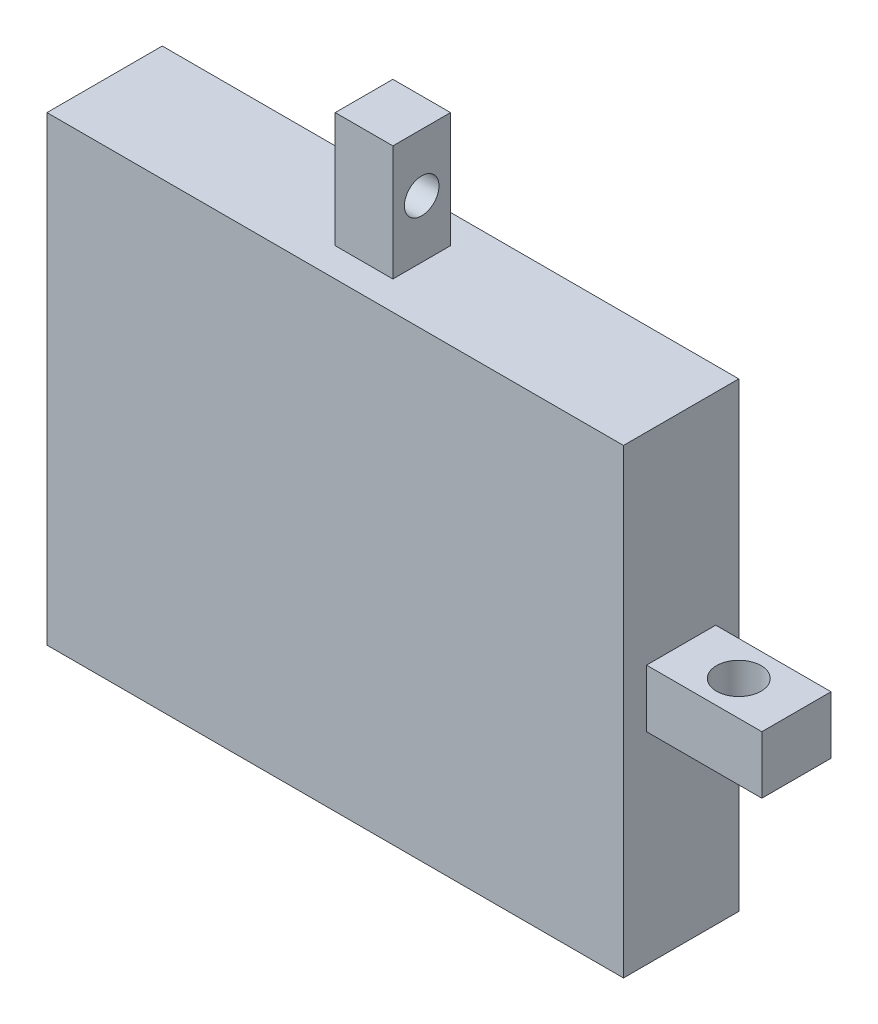
SolidWorks part; units mm, degrees
ref_plane "Front Plane" through (0, 0, 0) normal (0, 0, 1) x (1, 0, 0)
ref_plane "Top Plane" through (0, 0, 0) normal (0, 1, 0) x (1, 0, 0)
ref_plane "Right Plane" through (0, 0, 0) normal (1, 0, 0) x (0, 0, -1)
sketch "Sketch1" plane through (669.8418, 0, 0) normal (0, 0, 1) x (1, 0, 0)
  line L1 (-696.3103, 457.6379) -> (-646.3103, 457.6379)
  line L2 (-696.3103, 457.6379) -> (-696.3103, 417.6379)
  line L3 (-696.3103, 417.6379) -> (-646.3103, 417.6379)
  line L4 (-646.3103, 457.6379) -> (-646.3103, 417.6379)
  dimension "50" = 50
  dimension "D2" = 40
extrude "Boss-Extrude1" add sketch "Sketch1" along normal blind 10
sketch "Sketch5" plane through (23.5315, 0, 0) normal (1, 0, 0) x (0, 0, -1)
  line L0 (0, 417.6379) -> (0, 457.6379) construction
  line L1 (-8, 445.1379) -> (-2, 445.1379)
  line L2 (-8, 445.1379) -> (-8, 440.1379)
  line L3 (-8, 440.1379) -> (-2, 440.1379)
  line L4 (-2, 445.1379) -> (-2, 440.1379)
  line L5 (-8, 435.1379) -> (-2, 435.1379)
  line L6 (-8, 435.1379) -> (-8, 430.1379)
  line L7 (-8, 430.1379) -> (-2, 430.1379)
  line L8 (-2, 435.1379) -> (-2, 430.1379)
  line L9 (-10, 417.6379) -> (-10, 457.6379) construction
  line L10 (0, 437.6379) -> (-10, 437.6379)
  line L11 (-2, 440.1379) -> (-2, 437.6379)
  line L12 (-8, 435.1379) -> (-8, 437.6379)
  dimension "D1" = 5
  dimension "D2" = 2
  dimension "D3" = 2
  dimension "D4" = 2
  dimension "D5" = 2
  dimension "D6" = 5
  dimension "D7" = 5
extrude "Boss-Extrude3" add sketch "Sketch5" along normal blind 10 contours L4 L1 L2 L3 | L8 L5 L6 L7
sketch "Sketch6" plane through (669.8418, 445.1379, 0) normal (0, 1, 0) x (1, 0, 0)
  line L1 (-646.3103, -8) -> (-646.3103, -2) construction
  line L2 (-646.3103, -5) -> (-636.3103, -5) construction
  line L3 (-636.3103, -8) -> (-636.3103, -2) construction
  line L4 (-641.3103, -8) -> (-641.3103, -2) construction
  line L5 (-636.3103, -8) -> (-646.3103, -8) construction
  line L6 (-636.3103, -2) -> (-646.3103, -2) construction
  circle A1 centre (-641.3103, -5) radius 2
extrude "Cut-Extrude1" cut sketch "Sketch6" against normal blind 20
sketch "Sketch8" plane through (-26.4685, 0, 0) normal (-1, 0, 0) x (0, 0, 1)
  line L1 (0, 417.6379) -> (10, 417.6379)
  line L2 (0, 417.6379) -> (0, 457.6379)
  line L3 (0, 457.6379) -> (10, 457.6379)
  line L4 (10, 417.6379) -> (10, 457.6379)
extrude "Cut-Extrude2" cut sketch "Sketch8" against normal blind 25
sketch "Sketch9" plane through (0, 435.1379, 0) normal (0, 1, 0) x (1, 0, 0)
  line L1 (23.5315, -8) -> (33.5315, -8)
  line L2 (23.5315, -8) -> (23.5315, -2)
  line L3 (23.5315, -2) -> (33.5315, -2)
  line L4 (33.5315, -8) -> (33.5315, -2)
  circle A0 centre (28.5315, -5) radius 1.9309
extrude "Boss-Extrude4" add sketch "Sketch9" along normal blind 5
sketch "Sketch10" plane through (0, 0, 8) normal (0, 0, 1) x (1, 0, 0)
  line L0 (23.5315, 417.6379) -> (23.5315, 457.6379) construction
  line L1 (33.5315, 430.1379) -> (23.5315, 430.1379)
  line L2 (33.5315, 430.1379) -> (33.5315, 435.1379)
  line L3 (33.5315, 435.1379) -> (23.5315, 435.1379)
  line L4 (23.5315, 430.1379) -> (23.5315, 435.1379)
  line L6 (33.5315, 445.1379) -> (23.5315, 445.1379)
  line L7 (33.5315, 445.1379) -> (33.5315, 440.1379)
  line L8 (33.5315, 440.1379) -> (23.5315, 440.1379)
  line L9 (23.5315, 445.1379) -> (23.5315, 440.1379)
  dimension "D1" = 5
  dimension "D2" = 5
extrude "Cut-Extrude3" cut sketch "Sketch10" against normal blind 15 contours L7 L6 L9 L8 | L2 L1 L4 L3
mirror "Mirror1" about plane through (-1.4685, 0, 0) normal (1, 0, 0) of "Boss-Extrude1"
sketch "Sketch11" plane through (0, 457.6379, 0) normal (0, 1, 0) x (1, 0, 0)
  line L0 (23.5315, 0) -> (-26.4685, 0) construction
  line L1 (-3.9685, -2.5) -> (1.0315, -2.5)
  line L2 (-3.9685, -2.5) -> (-3.9685, -7.5)
  line L3 (-3.9685, -7.5) -> (1.0315, -7.5)
  line L4 (1.0315, -2.5) -> (1.0315, -7.5)
  line L5 (23.5315, -10) -> (-26.4685, -10) construction
  line L6 (23.5315, -10) -> (23.5315, 0) construction
  line L7 (-26.4685, -10) -> (-26.4685, 0) construction
  dimension "D1" = 2.5
  dimension "D2" = 2.5
  dimension "D3" = 22.5
  dimension "D4" = 22.5
extrude "Boss-Extrude5" add sketch "Sketch11" along normal blind 10
sketch "Sketch12" plane through (1.0315, 0, 0) normal (1, 0, 0) x (0, 0, -1)
  line L0 (-5, 467.6379) -> (-5, 457.6379) construction
  line L1 (-7.5, 467.6379) -> (-2.5, 467.6379) construction
  line L2 (-7.5, 457.6379) -> (-2.5, 457.6379) construction
  line L3 (-2.5, 462.6379) -> (-7.5, 462.6379) construction
  line L4 (-2.5, 467.6379) -> (-2.5, 457.6379) construction
  line L5 (-7.5, 467.6379) -> (-7.5, 457.6379) construction
  circle A1 centre (-5, 462.6379) radius 1.5
  dimension "D1" = 3
extrude "Cut-Extrude4" cut sketch "Sketch12" against normal blind 10
